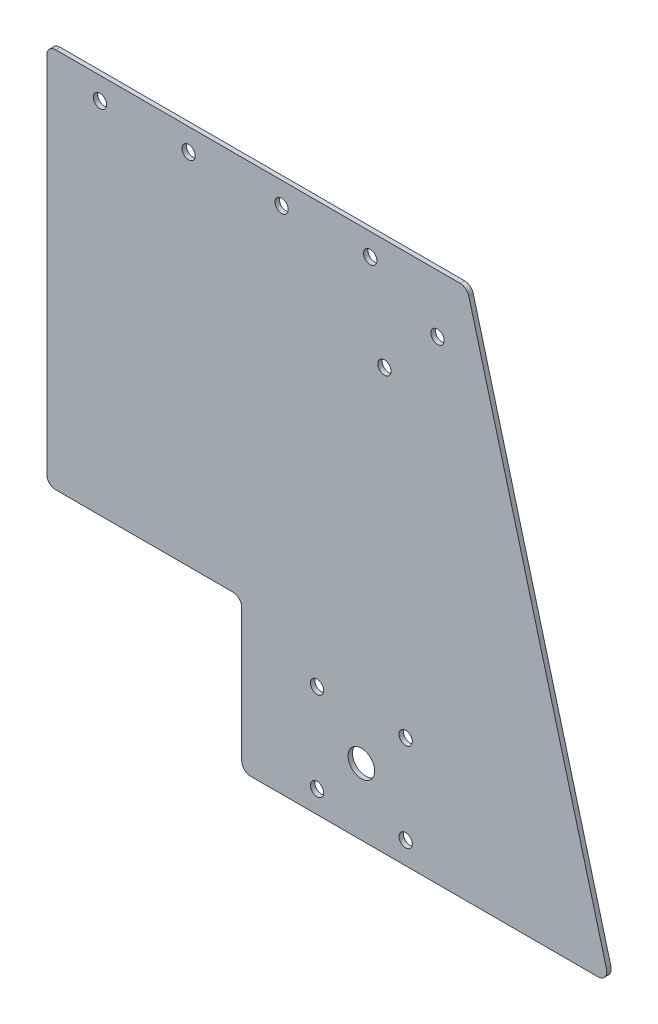
SolidWorks part; units mm, degrees
ref_plane "前视基准面" through (0, 0, 0) normal (0, 0, 1) x (1, 0, 0)
ref_plane "上视基准面" through (0, 0, 0) normal (0, 1, 0) x (1, 0, 0)
ref_plane "右视基准面" through (0, 0, 0) normal (1, 0, 0) x (0, 0, -1)
other "Configuration Table"
sketch "草图1" plane through (0, 0, 0) normal (0, 0, 1) x (1, 0, 0)
  line L0 (0, 0) -> (175, 0)
  line L1 (175, 0) -> (142.8461, 120)
  line L2 (142.8461, 120) -> (0, 120)
  line L3 (0, 120) -> (0, 0)
  line L5 (109, 5) -> (129, 5) construction
  line L6 (109, 5) -> (109, 25) construction
  line L7 (109, 25) -> (129, 25) construction
  line L8 (129, 5) -> (129, 25) construction
  line L9 (109, 5) -> (129, 25) construction
  line L10 (109, 25) -> (129, 5) construction
  circle A0 centre (129, 25) radius 1.5
  circle A1 centre (129, 5) radius 1.5
  circle A2 centre (119, 15) radius 3
  circle A3 centre (109, 5) radius 1.5
  circle A4 centre (109, 25) radius 1.5
  point P3 (119, 15)
  dimension "D1" = 3
  dimension "D2" = 6
  dimension "D3" = 20
  dimension "D4" = 15
  dimension "D5" = 75
  dimension "D6" = 109
  dimension "D7" = 175
  dimension "D8" = 120
extrude "凸台-拉伸1" add sketch "草图1" along normal blind 1
sketch "草图4" plane through (0, 0, 0) normal (0, 0, -1) x (-1, 0, 0)
  line L0 (-22, 40) -> (-22, 60) construction
  line L1 (-22, 101) -> (-22, 81) construction
  line L2 (0, 120) -> (0, 0) construction
  line L4 (0, 0) -> (-175, 0) construction
  circle A0 centre (-22, 101) radius 1.5
  circle A1 centre (-22, 81) radius 1.5
  circle A2 centre (-22, 60) radius 1.5
  circle A3 centre (-22, 40) radius 1.5
  dimension "D2" = 22
  dimension "D3" = 3
  dimension "D4" = 40
  dimension "D5" = 21
  dimension "D1" = 20
extrude "切除-拉伸2" cut sketch "草图4" against normal blind 4
sketch "草图5" plane through (0, 0, 0) normal (0, 0, -1) x (-1, 0, 0)
  line L0 (-136.2, 107) -> (-124.2, 95) construction
  line L2 (0, 120) -> (0, 0) construction
  line L3 (0, 0) -> (-175, 0) construction
  circle A0 centre (-136.2, 107) radius 1.5
  circle A1 centre (-124.2, 95) radius 1.5
  dimension "D3" = 3
  dimension "D4" = 95
  dimension "D5" = 136.2
  dimension "D1" = 12
  dimension "D2" = 12
extrude "切除-拉伸3" cut sketch "草图5" against normal blind 10
sketch "草图6" plane through (0, 0, 1) normal (0, 0, 1) x (1, 0, 0)
  line L1 (0, 0) -> (53, 0)
  line L2 (0, 0) -> (0, 34)
  line L3 (0, 34) -> (53, 34)
  line L4 (53, 0) -> (53, 34)
  dimension "D1" = 34
  dimension "D2" = 53
extrude "切除-拉伸4" cut sketch "草图6" against normal blind 10
sketch "草图7" plane through (0, 0, 1) normal (0, 0, 1) x (1, 0, 0)
  line L1 (53, 0) -> (92, 0)
  line L2 (53, 0) -> (53, 34)
  line L3 (53, 34) -> (92, 34)
  line L4 (92, 0) -> (92, 34)
  dimension "D1" = 39
  dimension "D2" = 34
extrude "切除-拉伸5" cut sketch "草图7" against normal blind 10
sketch "草图8" [suppressed] plane through (0, 0, 1) normal (0, 0, 1) x (1, 0, 0)
  line L1 (70, 81) -> (115, 81) construction
  line L2 (70, 81) -> (70, 62.5) construction
  line L3 (70, 62.5) -> (115, 62.5) construction
  line L4 (115, 81) -> (115, 62.5) construction
  line L5 (90, 34) -> (0, 34) construction
  line L6 (92.5, 81) -> (92.5, 62.5) construction
  line L7 (0, 120) -> (0, 34) construction
  circle A0 centre (115, 81) radius 1.5
  circle A1 centre (115, 62.5) radius 1.5
  circle A2 centre (70, 62.5) radius 1.5
  circle A3 centre (70, 81) radius 1.5
  dimension "D3" = 3
  dimension "D1" = 18.5
  dimension "D2" = 45
  dimension "D4" = 92.5
  dimension "D5" = 28.5
extrude "切除-拉伸6" [suppressed] cut sketch "草图8" against normal blind 10
sketch "草图9" [suppressed] plane through (0, 0, 1) normal (0, 0, 1) x (1, 0, 0)
  line L0 (92.5, 84.5) -> (92.5, 62.5) construction
  line L1 (70, 84.5) -> (115, 84.5) construction
  line L2 (70, 84.5) -> (70, 62.5) construction
  line L3 (70, 62.5) -> (115, 62.5) construction
  line L4 (115, 84.5) -> (115, 62.5) construction
  line L5 (0, 120) -> (0, 34) construction
  line L6 (92, 34) -> (0, 34) construction
  circle A0 centre (115, 84.5) radius 1.5
  circle A1 centre (115, 62.5) radius 1.5
  circle A2 centre (70, 62.5) radius 1.5
  circle A3 centre (70, 84.5) radius 1.5
  dimension "D5" = 3
  dimension "D1" = 92.5
  dimension "D2" = 28.5
  dimension "D3" = 45
  dimension "D4" = 22
extrude "切除-拉伸7" [suppressed] cut sketch "草图9" against normal blind 10
sketch "草图10" plane through (0, 0, 1) normal (0, 0, 1) x (1, 0, 0)
  line L0 (142.8461, 120) -> (0, 120) construction
  circle A0 centre (37, 104) radius 10
  circle A1 centre (22, 101) radius 1.5 construction
  dimension "D1" = 20
  dimension "D2" = 16
  dimension "D3" = 15
extrude "切除-拉伸8" cut sketch "草图10" against normal blind 10
sketch "草图11" [suppressed] plane through (0, 0, 1) normal (0, 0, 1) x (1, 0, 0)
  circle A0 centre (22, 40) radius 1.5 construction
  circle A1 centre (22, 60) radius 1.5 construction
  circle A2 centre (22, 81) radius 1.5 construction
  circle A3 centre (22, 101) radius 1.5 construction
  circle A4 centre (22, 40) radius 1.5
  circle A5 centre (22, 60) radius 1.5
  circle A6 centre (22, 81) radius 1.5
  circle A7 centre (22, 101) radius 1.5
extrude "凸台-拉伸2" [suppressed] add sketch "草图11" against normal blind 1
sketch "草图12" [suppressed] plane through (0, 0, 1) normal (0, 0, 1) x (1, 0, 0)
  line L0 (3, 74) -> (3, 54) construction
  line L2 (0, 120) -> (0, 34) construction
  line L3 (92, 34) -> (0, 34) construction
  circle A0 centre (3, 74) radius 1.5
  circle A1 centre (3, 54) radius 1.5
  dimension "D1" = 3
  dimension "D3" = 20
  dimension "D2" = 20
  dimension "D4" = 3
extrude "切除-拉伸9" [suppressed] cut sketch "草图12" against normal blind 1
sketch "草图13" plane through (0, 0, 1) normal (0, 0, 1) x (1, 0, 0)
  line L0 (101, 115) -> (121, 115) construction
  line L1 (142.8461, 120) -> (0, 120) construction
  line L2 (60, 115) -> (80, 115) construction
  line L3 (0, 120) -> (0, 34) construction
  circle A0 centre (121, 115) radius 1.5
  circle A1 centre (101, 115) radius 1.5
  circle A2 centre (80, 115) radius 1.5
  circle A3 centre (60, 115) radius 1.5
  circle A4 centre (45, 115) radius 1.5
  circle A5 centre (25, 115) radius 1.5
  dimension "D3" = 3
  dimension "D4" = 21
  dimension "D5" = 60
  dimension "D6" = 15
  dimension "D7" = 20
  dimension "D1" = 5
  dimension "D2" = 20
extrude "切除-拉伸10" cut sketch "草图13" against normal blind 1
fillet "圆角1" radius 2 6 edges at (0, 34, 0.5) (142.8461, 120, 0.5) (175, 0, 0.5) (92, 0, 0.5) (92, 34, 0.5) (0, 120, 0.5)
sketch "草图15" [suppressed] plane through (0, 0, 0) normal (0, 0, -1) x (-1, 0, 0)
  line L0 (-142.8461, 120) -> (0, 120) construction
  line L1 (-113.75, 120) -> (-71.25, 120)
  line L2 (-113.75, 120) -> (-113.75, 98.5)
  line L3 (-113.75, 98.5) -> (-71.25, 98.5)
  line L4 (-71.25, 120) -> (-71.25, 98.5)
  line L5 (0, 120) -> (0, 34) construction
  dimension "D1" = 71.25
  dimension "D2" = 42.5
  dimension "D3" = 21.5
extrude "切除-拉伸11" [suppressed] cut sketch "草图15" against normal blind 10
sketch "草图16" [suppressed] plane through (0, 0, 0) normal (0, 0, -1) x (-1, 0, 0)
  line L0 (-60, 115) -> (-30, 115) construction
  circle A0 centre (-30, 115) radius 1.5 construction
  circle A1 centre (-60, 115) radius 1.5 construction
  circle A2 centre (-10, 115) radius 1.5
  circle A3 centre (-50, 115) radius 1.5 construction
  dimension "D2" = 20
  dimension "D3" = 20
  dimension "D1" = 30
extrude "切除-拉伸12" [suppressed] cut sketch "草图16" against normal blind 10
fillet "圆角2" [suppressed] radius 2
fillet "圆角3" [suppressed] radius 2
sketch "草图17" [suppressed] plane through (0, 0, 1) normal (0, 0, 1) x (1, 0, 0)
  line L0 (141.3114, 120) -> (2, 120) construction
  line L1 (71.25, 120) -> (113.75, 120)
  line L2 (71.25, 120) -> (71.25, 113.5)
  line L3 (71.25, 113.5) -> (113.75, 113.5)
  line L4 (113.75, 120) -> (113.75, 113.5)
  line L5 (0, 118) -> (0, 36) construction
  line L6 (100, 107) -> (85, 107) construction
  line L7 (92.5, 107) -> (92.5, 113.5) construction
  circle A0 centre (85, 107) radius 1.75
  circle A1 centre (100, 107) radius 1.75
  dimension "D4" = 3.5
  dimension "D1" = 71.25
  dimension "D2" = 113.75
  dimension "D3" = 6.5
  dimension "D5" = 13
  dimension "D6" = 15
extrude "切除-拉伸13" [suppressed] cut sketch "草图17" against normal blind 10
sketch "草图18" [suppressed] plane through (0, 0, 1) normal (0, 0, 1) x (1, 0, 0)
  line L0 (71.25, 109.25) -> (113.75, 109.25) construction
  line L1 (71.25, 118) -> (71.25, 100.5) construction
  line L2 (113.75, 100.5) -> (113.75, 118) construction
  line L3 (92.5, 109.25) -> (92.5, 90.5) construction
  line L4 (92.5, 90.5) -> (92.5, 79.5) construction
  line L5 (73.25, 98.5) -> (111.75, 98.5) construction
  circle A0 centre (92.5, 90.5) radius 1.5
  circle A1 centre (92.5, 79.5) radius 1.5
  dimension "D2" = 3
  dimension "D3" = 8
  dimension "D1" = 11
extrude "切除-拉伸14" [suppressed] cut sketch "草图18" against normal blind 10
fillet "圆角4" [suppressed] radius 2
sketch "草图19" [suppressed] plane through (0, 0, 0) normal (0, 0, -1) x (-1, 0, 0)
  line L0 (-3, 54) -> (-3, 74) construction
  line L1 (-3, 74) -> (-10, 74) construction
  line L2 (-10, 74) -> (-10, 54) construction
  line L3 (-10, 54) -> (-3, 54) construction
  circle A0 centre (-10, 74) radius 1.5
  circle A1 centre (-10, 54) radius 1.5
  circle A2 centre (-3, 74) radius 1.5 construction
  dimension "D1" = 7
extrude "切除-拉伸15" [suppressed] cut sketch "草图19" against normal blind 10
sketch "草图20" plane through (0, 0, 0) normal (0, 0, -1) x (-1, 0, 0)
  circle A0 centre (-37, 104) radius 10 construction
  circle A1 centre (-37, 104) radius 10
extrude "凸台-拉伸3" add sketch "草图20" against normal blind 1
sketch "草图21" plane through (0, 0, 0) normal (0, 0, -1) x (-1, 0, 0)
  line L1 (-48, 120) -> (0, 120)
  line L2 (-48, 120) -> (-48, 34)
  line L3 (-48, 34) -> (0, 34)
  line L4 (0, 120) -> (0, 34)
  line L5 (-90, 34) -> (-2, 34) construction
  line L6 (0, 118) -> (0, 36) construction
  dimension "D1" = 48
  dimension "D2" = 86
extrude "切除-拉伸16" cut sketch "草图21" against normal blind 10
fillet "圆角5" radius 2 2 edges at (48, 34, 0.5) (48, 120, 0.5)
sketch "草图22" [suppressed] plane through (0, 0, 0) normal (0, 0, -1) x (-1, 0, 0)
  line L0 (-115.75, 120) -> (-69.25, 120)
  line L10 (-90, 34) -> (-50, 34)
  line L11 (-48, 36) -> (-48, 118)
  line L12 (-50, 120) -> (-69.25, 120)
  line L13 (-71.25, 118) -> (-71.25, 100.5)
  line L14 (-73.25, 98.5) -> (-111.75, 98.5)
  line L15 (-113.75, 100.5) -> (-113.75, 118)
  line L16 (-115.75, 120) -> (-141.3114, 120)
  line L17 (-143.2433, 118.5176) -> (-174.3254, 2.5176)
  line L18 (-172.3935, 0) -> (-94, 0)
  line L19 (-92, 2) -> (-92, 32)
  line L20 (-90, 34) -> (-50, 34)
  line L21 (-48, 36) -> (-48, 118)
  line L22 (-50, 120) -> (-69.25, 120)
  line L23 (-71.25, 118) -> (-71.25, 100.5)
  line L24 (-73.25, 98.5) -> (-111.75, 98.5)
  line L25 (-113.75, 100.5) -> (-113.75, 118)
  line L26 (-115.75, 120) -> (-141.3114, 120)
  line L27 (-143.2433, 118.5176) -> (-174.3254, 2.5176)
  line L28 (-172.3935, 0) -> (-94, 0)
  line L29 (-92, 2) -> (-92, 32)
  arc A10 (-50, 34) -> (-48, 36) centre (-50, 36) ccw
  arc A11 (-48, 118) -> (-50, 120) centre (-50, 118) ccw
  arc A12 (-69.25, 120) -> (-71.25, 118) centre (-69.25, 118) ccw
  arc A13 (-73.25, 98.5) -> (-71.25, 100.5) centre (-73.25, 100.5) ccw
  arc A14 (-113.75, 100.5) -> (-111.75, 98.5) centre (-111.75, 100.5) ccw
  arc A15 (-113.75, 118) -> (-115.75, 120) centre (-115.75, 118) ccw
  arc A16 (-141.3114, 120) -> (-143.2433, 118.5176) centre (-141.3114, 118) ccw
  arc A17 (-174.3254, 2.5176) -> (-172.3935, 0) centre (-172.3935, 2) ccw
  arc A18 (-94, 0) -> (-92, 2) centre (-94, 2) ccw
  arc A19 (-90, 34) -> (-92, 32) centre (-90, 32) ccw
  arc A20 (-50, 34) -> (-48, 36) centre (-50, 36) ccw
  arc A21 (-48, 118) -> (-50, 120) centre (-50, 118) ccw
  arc A22 (-69.25, 120) -> (-71.25, 118) centre (-69.25, 118) ccw
  arc A23 (-73.25, 98.5) -> (-71.25, 100.5) centre (-73.25, 100.5) ccw
  arc A24 (-113.75, 100.5) -> (-111.75, 98.5) centre (-111.75, 100.5) ccw
  arc A25 (-113.75, 118) -> (-115.75, 120) centre (-115.75, 118) ccw
  arc A26 (-141.3114, 120) -> (-143.2433, 118.5176) centre (-141.3114, 118) ccw
  arc A27 (-174.3254, 2.5176) -> (-172.3935, 0) centre (-172.3935, 2) ccw
  arc A28 (-94, 0) -> (-92, 2) centre (-94, 2) ccw
  arc A29 (-90, 34) -> (-92, 32) centre (-90, 32) ccw
  arc M36 (-69.25, 120) -> (-71.25, 118) centre (-69.25, 118) ccw
  line M37 (-71.25, 118) -> (-71.25, 100.5)
  arc M38 (-71.25, 100.5) -> (-73.25, 98.5) centre (-73.25, 100.5) cw
  line M39 (-73.25, 98.5) -> (-111.75, 98.5)
  arc M40 (-111.75, 98.5) -> (-113.75, 100.5) centre (-111.75, 100.5) cw
  line M41 (-113.75, 100.5) -> (-113.75, 118)
  arc M42 (-113.75, 118) -> (-115.75, 120) centre (-115.75, 118) ccw
  dimension "D1" = 0
extrude "凸台-拉伸4" [suppressed] add sketch "草图22" against normal blind 1 contours L0 M42 M41 M40 M39 M38 M37 M36
sketch "草图23" [suppressed] plane through (0, 0, 0) normal (0, 0, -1) x (-1, 0, 0)
  line L0 (-121, 115) -> (-60, 115) construction
  circle A0 centre (-80, 115) radius 1.5
  circle A1 centre (-101, 115) radius 1.5
  circle A2 centre (-121, 115) radius 1.5 construction
  circle A3 centre (-60, 115) radius 1.5 construction
  dimension "D1" = 20
  dimension "D2" = 20
extrude "切除-拉伸17" [suppressed] cut sketch "草图23" against normal blind 1
